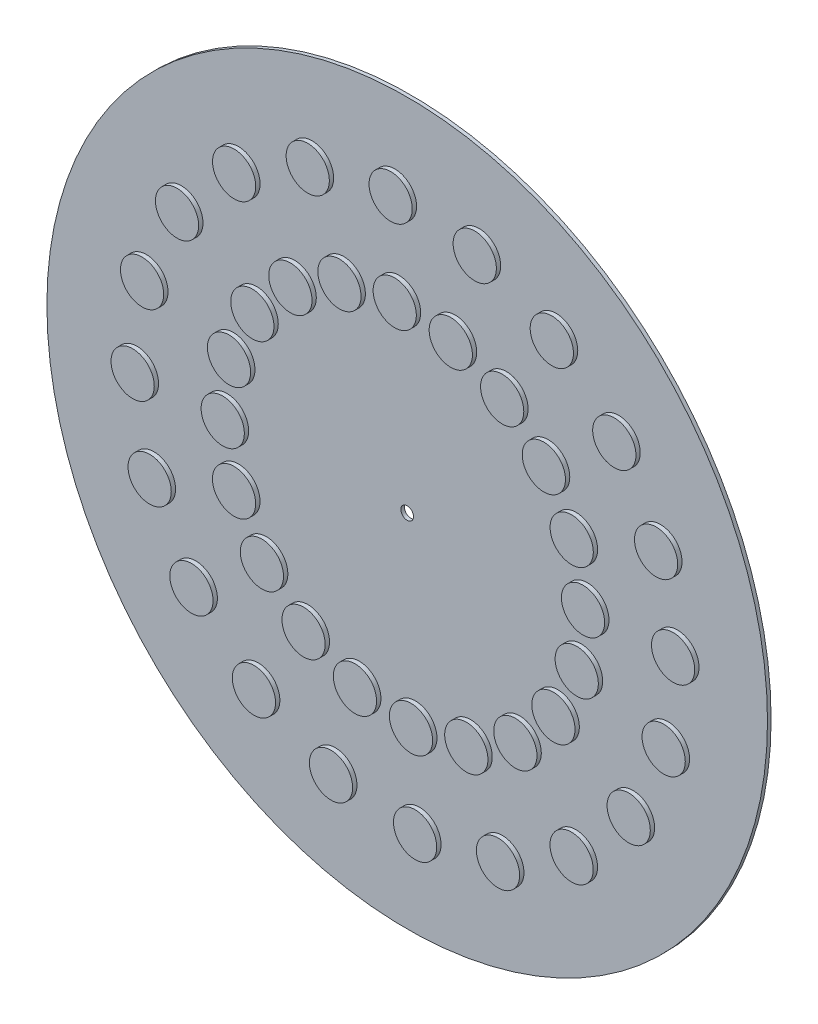
SolidWorks part; units mm, degrees
ref_plane "Front Plane" through (0, 0, 0) normal (0, 0, 1) x (1, 0, 0)
ref_plane "Top Plane" through (0, 0, 0) normal (0, 1, 0) x (1, 0, 0)
ref_plane "Right Plane" through (0, 0, 0) normal (1, 0, 0) x (0, 0, -1)
sketch "Sketch1" plane through (0, 0, 0) normal (0, 0, 1) x (1, 0, 0)
  circle A0 centre (0, 0) radius 100
  circle A1 centre (0, 0) radius 1.75
  dimension "D1" = 3.5
  dimension "D2" = 200
extrude "Boss-Extrude1" add sketch "Sketch1" along normal blind 1
sketch "Sketch2" plane through (0, 0, 1) normal (0, 0, 1) x (1, 0, 0)
  line L0 (0, 0) -> (-3.396, 75) construction
  line L1 (0, 0) -> (19.9464, 72.3787) construction
  line L2 (0, 0) -> (41.3364, 62.6724) construction
  line L3 (0, 0) -> (58.6801, 46.8313) construction
  line L4 (0, 0) -> (70.2798, 26.4061) construction
  line L5 (0, 0) -> (75, 3.396) construction
  line L6 (0, 0) -> (72.3787, -19.9464) construction
  line L7 (0, 0) -> (62.6724, -41.3364) construction
  line L8 (0, 0) -> (46.8313, -58.6801) construction
  line L9 (0, 0) -> (26.4061, -70.2798) construction
  line L10 (0, 0) -> (3.396, -75) construction
  line L11 (0, 0) -> (-19.9464, -72.3787) construction
  line L12 (0, 0) -> (-41.3364, -62.6724) construction
  line L13 (0, 0) -> (-58.6801, -46.8313) construction
  line L14 (0, 0) -> (-70.2798, -26.4061) construction
  line L15 (0, 0) -> (-75, -3.396) construction
  line L16 (0, 0) -> (-72.3787, 19.9464) construction
  line L17 (0, 0) -> (-62.6724, 41.3364) construction
  line L18 (0, 0) -> (-46.8313, 58.6801) construction
  line L19 (0, 0) -> (-26.4061, 70.2798) construction
  circle A0 centre (-3.396, 75) radius 6
  circle A1 centre (19.9464, 72.3787) radius 6
  circle A2 centre (41.3364, 62.6724) radius 6
  circle A3 centre (58.6801, 46.8313) radius 6
  circle A4 centre (70.2798, 26.4061) radius 6
  circle A5 centre (75, 3.396) radius 6
  circle A6 centre (72.3787, -19.9464) radius 6
  circle A7 centre (62.6724, -41.3364) radius 6
  circle A8 centre (46.8313, -58.6801) radius 6
  circle A9 centre (26.4061, -70.2798) radius 6
  circle A10 centre (3.396, -75) radius 6
  circle A11 centre (-19.9464, -72.3787) radius 6
  circle A12 centre (-41.3364, -62.6724) radius 6
  circle A13 centre (-58.6801, -46.8313) radius 6
  circle A14 centre (-70.2798, -26.4061) radius 6
  circle A15 centre (-75, -3.396) radius 6
  circle A16 centre (-72.3787, 19.9464) radius 6
  circle A17 centre (-62.6724, 41.3364) radius 6
  circle A18 centre (-46.8313, 58.6801) radius 6
  circle A19 centre (-26.4061, 70.2798) radius 6
  circle A20 centre (-2.264, 50) radius 6
  circle A21 centre (13.2976, 48.2524) radius 6
  circle A22 centre (27.5576, 41.7816) radius 6
  circle A23 centre (39.1201, 31.2209) radius 6
  circle A24 centre (46.8532, 17.6041) radius 6
  circle A25 centre (50, 2.264) radius 6
  circle A26 centre (48.2524, -13.2976) radius 6
  circle A27 centre (41.7816, -27.5576) radius 6
  circle A28 centre (31.2209, -39.1201) radius 6
  circle A29 centre (17.6041, -46.8532) radius 6
  circle A30 centre (2.264, -50) radius 6
  circle A31 centre (-13.2976, -48.2524) radius 6
  circle A32 centre (-27.5576, -41.7816) radius 6
  circle A33 centre (-39.1201, -31.2209) radius 6
  circle A34 centre (-46.8532, -17.6041) radius 6
  circle A35 centre (-50, -2.264) radius 6
  circle A36 centre (-48.2524, 13.2976) radius 6
  circle A37 centre (-41.7816, 27.5576) radius 6
  circle A38 centre (-31.2209, 39.1201) radius 6
  circle A39 centre (-17.6041, 46.8532) radius 6
  point P24 (0, 0)
  point P64 (0, 0)
  point P105 (0, 0)
  dimension "D3" = 12
  dimension "D5" = 12
  dimension "D1" = 75
  dimension "D6" = 50
  dimension "D2" = 20
  dimension "D4" = 20
  dimension "D7" = 20
extrude "Boss-Extrude2" add sketch "Sketch2" along normal blind 1.2 contours A18 | A19 | A16 | A15 | A14 | A13 | A12 | A11 | A10 | A9 | A8 | A7 | A6 | A5 | A4 | A3 | A2 | A1 | A0 | A39 | A20 | A21 | A22 | A23 | A24 | A25 | A26 | A27 | A28 | A29 | A30 | A31 | A32 | A33 | A34 | A35 | A36 | A37 | A38 | A17
